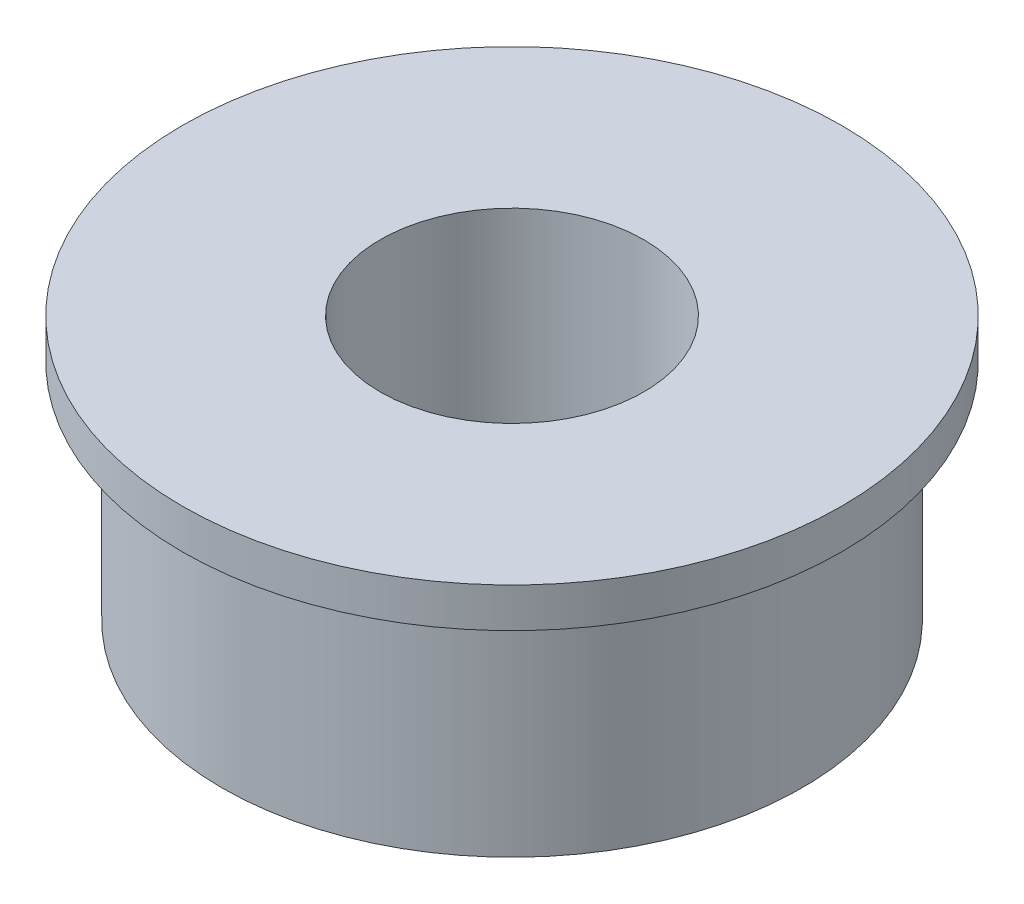
SolidWorks part; units mm, degrees
ref_plane "Front Plane" through (0, 0, 0) normal (0, 0, 1) x (1, 0, 0)
ref_plane "Top Plane" through (0, 0, 0) normal (0, 1, 0) x (1, 0, 0)
ref_plane "Right Plane" through (0, 0, 0) normal (1, 0, 0) x (0, 0, -1)
sketch "Sketch1" plane through (0, 0, 0) normal (0, 0, 1) x (1, 0, 0)
  line L0 (0, 5.7552) -> (0, -2.7344) construction
  line L1 (-2.5, 0) -> (-5.5, 0)
  line L2 (-5.5, 0) -> (-5.5, 4.25)
  line L3 (-5.5, 4.25) -> (-6.25, 4.25)
  line L4 (-6.25, 4.25) -> (-6.25, 5)
  line L5 (-6.25, 5) -> (-2.5, 5)
  line L6 (-2.5, 5) -> (-2.5, 0)
  point P5 (-5.5, 4.2763)
  dimension "D1" = 5
  dimension "D2" = 11
  dimension "D3" = 12.5
  dimension "D4" = 5
  dimension "D5" = 0.75
revolve "Revolve1" add sketch "Sketch1" angle 360 about L0
